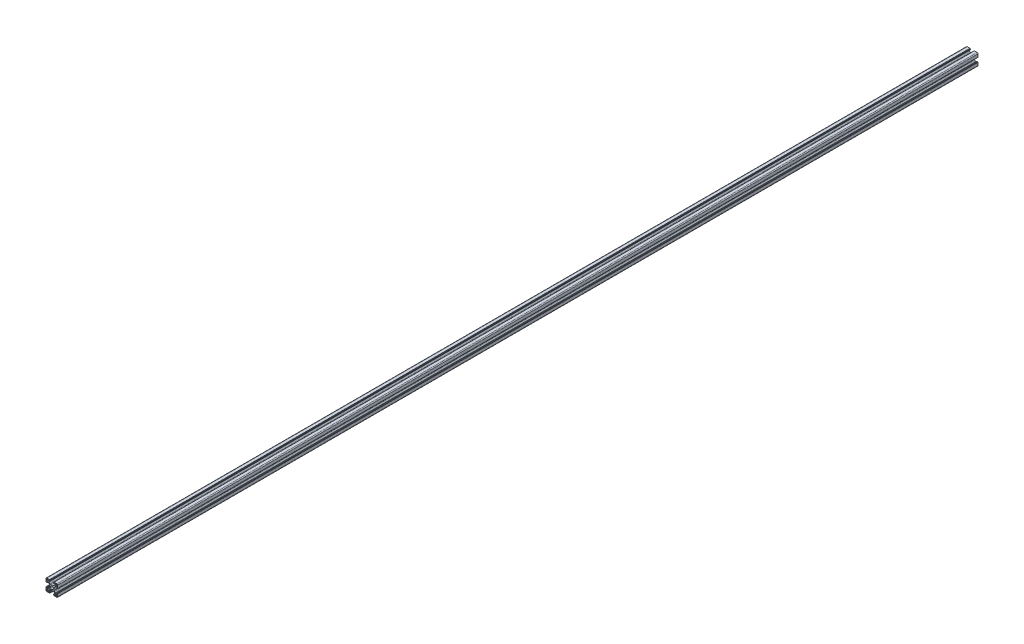
SolidWorks part; units mm, degrees
material "1060 Сплав"
ref_plane "Спереди" through (0, 0, 0) normal (0, 0, 1) x (1, 0, 0)
ref_plane "Сверху" through (0, 0, 0) normal (0, 1, 0) x (1, 0, 0)
ref_plane "Справа" through (0, 0, 0) normal (1, 0, 0) x (0, 0, -1)
sketch "Эскиз1" plane through (0, 0, 0) normal (0, 0, 1) x (1, 0, 0)
  line L0 (9.3595, 9.1357) -> (6.3595, 6.1357) construction
  line L1 (0.2595, 4.0357) -> (2.1582, 4.0357)
  line L2 (0.2595, 0.0357) -> (10.2595, 10.0357) construction
  line L3 (7.8595, 7.6357) -> (6.3595, 9.1357) construction
  line L4 (3.5725, 4.6215) -> (4.8737, 5.9227)
  line L5 (7.1595, 6.1357) -> (8.5595, 6.1357)
  line L6 (6.3595, 6.9357) -> (6.3595, 8.3357)
  line L7 (8.5595, 9.1357) -> (7.1595, 9.1357)
  line L8 (5.4595, 8.2357) -> (5.4595, 7.3369)
  line L9 (4.0227, 8.1089) -> (4.503, 8.5893)
  line L10 (3.4595, 9.5848) -> (3.9595, 9.5848)
  line L11 (3.8459, 8.0357) -> (3.5595, 8.0357)
  line L12 (4.8566, 8.7357) -> (4.9595, 8.7357)
  line L13 (3.9595, 9.8857) -> (3.9595, 9.5848)
  line L14 (3.3095, 9.4348) -> (3.3095, 8.2857)
  line L15 (8.7595, 10.0357) -> (4.1095, 10.0357)
  line L16 (9.3595, 8.3357) -> (9.3595, 6.9357)
  line L17 (10.2595, 8.5357) -> (10.2595, 3.8857)
  line L18 (9.6585, 3.0857) -> (8.5095, 3.0857)
  line L19 (10.1095, 3.7357) -> (9.8085, 3.7357)
  line L20 (8.9595, 4.6328) -> (8.9595, 4.7357)
  line L21 (8.2595, 3.6221) -> (8.2595, 3.3357)
  line L22 (9.8085, 3.2357) -> (9.8085, 3.7357)
  line L23 (8.3327, 3.7989) -> (8.813, 4.2793)
  line L24 (8.4595, 5.2357) -> (7.5607, 5.2357)
  line L25 (4.8452, 3.3487) -> (6.1465, 4.6499)
  line L26 (4.2595, 0.0357) -> (4.2595, 1.9345)
  line L27 (4.2595, 0.0357) -> (4.2595, -1.8631)
  line L28 (4.8452, -3.2773) -> (6.1465, -4.5785)
  line L29 (6.3595, -6.8643) -> (6.3595, -8.2643)
  line L30 (7.1595, -6.0643) -> (8.5595, -6.0643)
  line L31 (9.3595, -8.2643) -> (9.3595, -6.8643)
  line L32 (8.4595, -5.1643) -> (7.5607, -5.1643)
  line L33 (8.3327, -3.7275) -> (8.813, -4.2079)
  line L34 (9.8085, -3.1643) -> (9.8085, -3.6643)
  line L35 (8.2595, -3.5507) -> (8.2595, -3.2643)
  line L36 (8.9595, -4.5614) -> (8.9595, -4.6643)
  line L37 (10.1095, -3.6643) -> (9.8085, -3.6643)
  line L38 (9.6585, -3.0143) -> (8.5095, -3.0143)
  line L39 (10.2595, -8.4643) -> (10.2595, -3.8143)
  line L40 (8.5595, -9.0643) -> (7.1595, -9.0643)
  line L41 (8.7595, -9.9643) -> (4.1095, -9.9643)
  line L42 (3.3095, -9.3634) -> (3.3095, -8.2143)
  line L43 (3.9595, -9.8143) -> (3.9595, -9.5134)
  line L44 (4.8566, -8.6643) -> (4.9595, -8.6643)
  line L45 (3.8459, -7.9643) -> (3.5595, -7.9643)
  line L46 (3.4595, -9.5134) -> (3.9595, -9.5134)
  line L47 (4.0227, -8.0375) -> (4.503, -8.5179)
  line L48 (5.4595, -8.1643) -> (5.4595, -7.2655)
  line L49 (3.5725, -4.5501) -> (4.8737, -5.8513)
  line L50 (0.2595, -3.9643) -> (2.1582, -3.9643)
  line L51 (9.3595, -9.0643) -> (6.3595, -6.0643) construction
  line L52 (0.2595, 0.0357) -> (10.2595, -9.9643) construction
  line L53 (7.8595, -7.5643) -> (9.3595, -6.0643) construction
  line L54 (0.2595, -3.9643) -> (-1.6393, -3.9643)
  line L55 (-3.0535, -4.5501) -> (-4.3548, -5.8513)
  line L56 (-6.6405, -6.0643) -> (-8.0405, -6.0643)
  line L57 (-5.8405, -6.8643) -> (-5.8405, -8.2643)
  line L58 (-8.0405, -9.0643) -> (-6.6405, -9.0643)
  line L59 (-4.9405, -8.1643) -> (-4.9405, -7.2655)
  line L60 (-3.5038, -8.0375) -> (-3.9841, -8.5179)
  line L61 (-2.9405, -9.5134) -> (-3.4405, -9.5134)
  line L62 (-3.327, -7.9643) -> (-3.0405, -7.9643)
  line L63 (-4.3376, -8.6643) -> (-4.4405, -8.6643)
  line L64 (-3.4405, -9.8143) -> (-3.4405, -9.5134)
  line L65 (-2.7905, -9.3634) -> (-2.7905, -8.2143)
  line L66 (-8.2405, -9.9643) -> (-3.5905, -9.9643)
  line L67 (-8.8405, -8.2643) -> (-8.8405, -6.8643)
  line L68 (-9.7405, -8.4643) -> (-9.7405, -3.8143)
  line L69 (-9.1396, -3.0143) -> (-7.9905, -3.0143)
  line L70 (-9.5905, -3.6643) -> (-9.2896, -3.6643)
  line L71 (-8.4405, -4.5614) -> (-8.4405, -4.6643)
  line L72 (-7.7405, -3.5507) -> (-7.7405, -3.2643)
  line L73 (-9.2896, -3.1643) -> (-9.2896, -3.6643)
  line L74 (-7.8138, -3.7275) -> (-8.2941, -4.2079)
  line L75 (-7.9405, -5.1643) -> (-7.0418, -5.1643)
  line L76 (-4.3263, -3.2773) -> (-5.6275, -4.5785)
  line L77 (-3.7405, 0.0357) -> (-3.7405, -1.8631)
  line L78 (-8.8405, -9.0643) -> (-5.8405, -6.0643) construction
  line L79 (0.2595, 0.0357) -> (-9.7405, -9.9643) construction
  line L80 (-7.3405, -7.5643) -> (-5.8405, -9.0643) construction
  line L81 (-3.7405, 0.0357) -> (-3.7405, 1.9345)
  line L82 (-4.3263, 3.3487) -> (-5.6275, 4.6499)
  line L83 (-5.8405, 6.9357) -> (-5.8405, 8.3357)
  line L84 (-6.6405, 6.1357) -> (-8.0405, 6.1357)
  line L85 (-8.8405, 8.3357) -> (-8.8405, 6.9357)
  line L86 (-7.9405, 5.2357) -> (-7.0418, 5.2357)
  line L87 (-7.8138, 3.7989) -> (-8.2941, 4.2793)
  line L88 (-9.2896, 3.2357) -> (-9.2896, 3.7357)
  line L89 (-7.7405, 3.6221) -> (-7.7405, 3.3357)
  line L90 (-8.4405, 4.6328) -> (-8.4405, 4.7357)
  line L91 (-9.5905, 3.7357) -> (-9.2896, 3.7357)
  line L92 (-9.1396, 3.0857) -> (-7.9905, 3.0857)
  line L93 (-9.7405, 8.5357) -> (-9.7405, 3.8857)
  line L94 (-8.0405, 9.1357) -> (-6.6405, 9.1357)
  line L95 (-8.2405, 10.0357) -> (-3.5905, 10.0357)
  line L96 (-2.7905, 9.4348) -> (-2.7905, 8.2857)
  line L97 (-3.4405, 9.8857) -> (-3.4405, 9.5848)
  line L98 (-4.3376, 8.7357) -> (-4.4405, 8.7357)
  line L99 (-3.327, 8.0357) -> (-3.0405, 8.0357)
  line L100 (-2.9405, 9.5848) -> (-3.4405, 9.5848)
  line L101 (-3.5038, 8.1089) -> (-3.9841, 8.5893)
  line L102 (-4.9405, 8.2357) -> (-4.9405, 7.3369)
  line L103 (-3.0535, 4.6215) -> (-4.3548, 5.9227)
  line L104 (0.2595, 4.0357) -> (-1.6393, 4.0357)
  line L105 (-11.5046, 0.0357) -> (11.7638, 0.0357) construction
  line L106 (-8.8405, 9.1357) -> (-5.8405, 6.1357) construction
  line L107 (0.2595, -12.0507) -> (0.2595, 10.7546) construction
  line L108 (0.2595, 0.0357) -> (-9.7405, 10.0357) construction
  line L109 (-7.3405, 7.6357) -> (-8.8405, 6.1357) construction
  arc A0 (9.3595, 8.3357) -> (8.5595, 9.1357) centre (8.5595, 8.3357) ccw
  arc A1 (7.1595, 9.1357) -> (6.3595, 8.3357) centre (7.1595, 8.3357) ccw
  arc A2 (7.1595, 6.1357) -> (6.3595, 6.9357) centre (7.1595, 6.9357) cw
  arc A3 (8.7595, 10.0357) -> (10.2595, 8.5357) centre (8.7595, 8.5357) cw
  arc A4 (3.4595, 9.5848) -> (3.3095, 9.4348) centre (3.4595, 9.4348) ccw
  arc A5 (4.1095, 10.0357) -> (3.9595, 9.8857) centre (4.1095, 9.8857) ccw
  arc A6 (3.8459, 8.0357) -> (4.0227, 8.1089) centre (3.8459, 8.2857) ccw
  arc A7 (3.5595, 8.0357) -> (3.3095, 8.2857) centre (3.5595, 8.2857) cw
  arc A8 (4.503, 8.5893) -> (4.8566, 8.7357) centre (4.8566, 8.2357) cw
  arc A9 (4.9595, 8.7357) -> (5.4595, 8.2357) centre (4.9595, 8.2357) cw
  arc A10 (2.7595, 0.0357) -> (0.2595, 2.5357) centre (0.2595, 0.0357) ccw
  arc A11 (2.1582, 4.0357) -> (3.5725, 4.6215) centre (2.1582, 6.0357) ccw
  arc A12 (5.4595, 7.3369) -> (4.8737, 5.9227) centre (3.4595, 7.3369) cw
  arc A13 (9.3595, 6.9357) -> (8.5595, 6.1357) centre (8.5595, 6.9357) cw
  arc A14 (8.9595, 4.7357) -> (8.4595, 5.2357) centre (8.4595, 4.7357) ccw
  arc A15 (8.813, 4.2793) -> (8.9595, 4.6328) centre (8.4595, 4.6328) ccw
  arc A16 (8.2595, 3.3357) -> (8.5095, 3.0857) centre (8.5095, 3.3357) ccw
  arc A17 (8.2595, 3.6221) -> (8.3327, 3.7989) centre (8.5095, 3.6221) cw
  arc A18 (10.2595, 3.8857) -> (10.1095, 3.7357) centre (10.1095, 3.8857) cw
  arc A19 (9.8085, 3.2357) -> (9.6585, 3.0857) centre (9.6585, 3.2357) cw
  arc A20 (7.5607, 5.2357) -> (6.1465, 4.6499) centre (7.5607, 3.2357) ccw
  arc A21 (4.2595, 1.9345) -> (4.8452, 3.3487) centre (6.2595, 1.9345) cw
  arc A22 (8.5595, -9.0643) -> (9.3595, -8.2643) centre (8.5595, -8.2643) ccw
  arc A23 (9.3595, -6.8643) -> (8.5595, -6.0643) centre (8.5595, -6.8643) ccw
  arc A24 (6.3595, -6.8643) -> (7.1595, -6.0643) centre (7.1595, -6.8643) cw
  arc A25 (10.2595, -8.4643) -> (8.7595, -9.9643) centre (8.7595, -8.4643) cw
  arc A26 (9.8085, -3.1643) -> (9.6585, -3.0143) centre (9.6585, -3.1643) ccw
  arc A27 (10.2595, -3.8143) -> (10.1095, -3.6643) centre (10.1095, -3.8143) ccw
  arc A28 (8.2595, -3.5507) -> (8.3327, -3.7275) centre (8.5095, -3.5507) ccw
  arc A29 (8.2595, -3.2643) -> (8.5095, -3.0143) centre (8.5095, -3.2643) cw
  arc A30 (8.813, -4.2079) -> (8.9595, -4.5614) centre (8.4595, -4.5614) cw
  arc A31 (8.9595, -4.6643) -> (8.4595, -5.1643) centre (8.4595, -4.6643) cw
  arc A32 (0.2595, -2.4643) -> (2.7595, 0.0357) centre (0.2595, 0.0357) ccw
  arc A33 (4.2595, -1.8631) -> (4.8452, -3.2773) centre (6.2595, -1.8631) ccw
  arc A34 (7.5607, -5.1643) -> (6.1465, -4.5785) centre (7.5607, -3.1643) cw
  arc A35 (7.1595, -9.0643) -> (6.3595, -8.2643) centre (7.1595, -8.2643) cw
  arc A36 (4.9595, -8.6643) -> (5.4595, -8.1643) centre (4.9595, -8.1643) ccw
  arc A37 (4.503, -8.5179) -> (4.8566, -8.6643) centre (4.8566, -8.1643) ccw
  arc A38 (3.5595, -7.9643) -> (3.3095, -8.2143) centre (3.5595, -8.2143) ccw
  arc A39 (3.8459, -7.9643) -> (4.0227, -8.0375) centre (3.8459, -8.2143) cw
  arc A40 (4.1095, -9.9643) -> (3.9595, -9.8143) centre (4.1095, -9.8143) cw
  arc A41 (3.4595, -9.5134) -> (3.3095, -9.3634) centre (3.4595, -9.3634) cw
  arc A42 (5.4595, -7.2655) -> (4.8737, -5.8513) centre (3.4595, -7.2655) ccw
  arc A43 (2.1582, -3.9643) -> (3.5725, -4.5501) centre (2.1582, -5.9643) cw
  arc A44 (-8.8405, -8.2643) -> (-8.0405, -9.0643) centre (-8.0405, -8.2643) ccw
  arc A45 (-6.6405, -9.0643) -> (-5.8405, -8.2643) centre (-6.6405, -8.2643) ccw
  arc A46 (-6.6405, -6.0643) -> (-5.8405, -6.8643) centre (-6.6405, -6.8643) cw
  arc A47 (-8.2405, -9.9643) -> (-9.7405, -8.4643) centre (-8.2405, -8.4643) cw
  arc A48 (-2.9405, -9.5134) -> (-2.7905, -9.3634) centre (-2.9405, -9.3634) ccw
  arc A49 (-3.5905, -9.9643) -> (-3.4405, -9.8143) centre (-3.5905, -9.8143) ccw
  arc A50 (-3.327, -7.9643) -> (-3.5038, -8.0375) centre (-3.327, -8.2143) ccw
  arc A51 (-3.0405, -7.9643) -> (-2.7905, -8.2143) centre (-3.0405, -8.2143) cw
  arc A52 (-3.9841, -8.5179) -> (-4.3376, -8.6643) centre (-4.3376, -8.1643) cw
  arc A53 (-4.4405, -8.6643) -> (-4.9405, -8.1643) centre (-4.4405, -8.1643) cw
  arc A54 (-2.2405, 0.0357) -> (0.2595, -2.4643) centre (0.2595, 0.0357) ccw
  arc A55 (-1.6393, -3.9643) -> (-3.0535, -4.5501) centre (-1.6393, -5.9643) ccw
  arc A56 (-4.9405, -7.2655) -> (-4.3548, -5.8513) centre (-2.9405, -7.2655) cw
  arc A57 (-8.8405, -6.8643) -> (-8.0405, -6.0643) centre (-8.0405, -6.8643) cw
  arc A58 (-8.4405, -4.6643) -> (-7.9405, -5.1643) centre (-7.9405, -4.6643) ccw
  arc A59 (-8.2941, -4.2079) -> (-8.4405, -4.5614) centre (-7.9405, -4.5614) ccw
  arc A60 (-7.7405, -3.2643) -> (-7.9905, -3.0143) centre (-7.9905, -3.2643) ccw
  arc A61 (-7.7405, -3.5507) -> (-7.8138, -3.7275) centre (-7.9905, -3.5507) cw
  arc A62 (-9.7405, -3.8143) -> (-9.5905, -3.6643) centre (-9.5905, -3.8143) cw
  arc A63 (-9.2896, -3.1643) -> (-9.1396, -3.0143) centre (-9.1396, -3.1643) cw
  arc A64 (-7.0418, -5.1643) -> (-5.6275, -4.5785) centre (-7.0418, -3.1643) ccw
  arc A65 (-3.7405, -1.8631) -> (-4.3263, -3.2773) centre (-5.7405, -1.8631) cw
  arc A66 (-8.0405, 9.1357) -> (-8.8405, 8.3357) centre (-8.0405, 8.3357) ccw
  arc A67 (-8.8405, 6.9357) -> (-8.0405, 6.1357) centre (-8.0405, 6.9357) ccw
  arc A68 (-5.8405, 6.9357) -> (-6.6405, 6.1357) centre (-6.6405, 6.9357) cw
  arc A69 (-9.7405, 8.5357) -> (-8.2405, 10.0357) centre (-8.2405, 8.5357) cw
  arc A70 (-9.2896, 3.2357) -> (-9.1396, 3.0857) centre (-9.1396, 3.2357) ccw
  arc A71 (-9.7405, 3.8857) -> (-9.5905, 3.7357) centre (-9.5905, 3.8857) ccw
  arc A72 (-7.7405, 3.6221) -> (-7.8138, 3.7989) centre (-7.9905, 3.6221) ccw
  arc A73 (-7.7405, 3.3357) -> (-7.9905, 3.0857) centre (-7.9905, 3.3357) cw
  arc A74 (-8.2941, 4.2793) -> (-8.4405, 4.6328) centre (-7.9405, 4.6328) cw
  arc A75 (-8.4405, 4.7357) -> (-7.9405, 5.2357) centre (-7.9405, 4.7357) cw
  arc A76 (0.2595, 2.5357) -> (-2.2405, 0.0357) centre (0.2595, 0.0357) ccw
  arc A77 (-3.7405, 1.9345) -> (-4.3263, 3.3487) centre (-5.7405, 1.9345) ccw
  arc A78 (-7.0418, 5.2357) -> (-5.6275, 4.6499) centre (-7.0418, 3.2357) cw
  arc A79 (-6.6405, 9.1357) -> (-5.8405, 8.3357) centre (-6.6405, 8.3357) cw
  arc A80 (-4.4405, 8.7357) -> (-4.9405, 8.2357) centre (-4.4405, 8.2357) ccw
  arc A81 (-3.9841, 8.5893) -> (-4.3376, 8.7357) centre (-4.3376, 8.2357) ccw
  arc A82 (-3.0405, 8.0357) -> (-2.7905, 8.2857) centre (-3.0405, 8.2857) ccw
  arc A83 (-3.327, 8.0357) -> (-3.5038, 8.1089) centre (-3.327, 8.2857) cw
  arc A84 (-3.5905, 10.0357) -> (-3.4405, 9.8857) centre (-3.5905, 9.8857) cw
  arc A85 (-2.9405, 9.5848) -> (-2.7905, 9.4348) centre (-2.9405, 9.4348) cw
  arc A86 (-4.9405, 7.3369) -> (-4.3548, 5.9227) centre (-2.9405, 7.3369) ccw
  arc A87 (-1.6393, 4.0357) -> (-3.0535, 4.6215) centre (-1.6393, 6.0357) cw
  point P0 (0.2595, 0.0357)
  point P9 (0.2595, 0.0357)
  point P40 (8.9595, 3.7357)
  point P93 (3.9595, -8.6643)
  point P144 (3.9595, 8.7357)
  point P152 (8.9595, -3.6643)
  point P153 (0.2595, -3.8886)
  point P154 (0.2595, 0.0357)
  point P189 (-8.4405, -3.6643)
  point P228 (-3.4405, -8.6643)
  point P229 (-3.6648, 0.0357)
  point P230 (0.2595, 0.0357)
  point P268 (-3.4405, 8.7357)
  point P273 (4.1837, 0.0357)
  point P306 (-8.4405, 3.7357)
  point P307 (0.2595, 3.96)
  point P309 (0.2595, 0.0357)
  dimension "D3" = 5
  dimension "D6" = 2
  dimension "D1" = 2
  dimension "D2" = 6
  dimension "D4" = 4
  dimension "D5" = 0.9
extrude "Бобышка-Вытянуть1" add sketch "Эскиз1" along normal blind 1570
